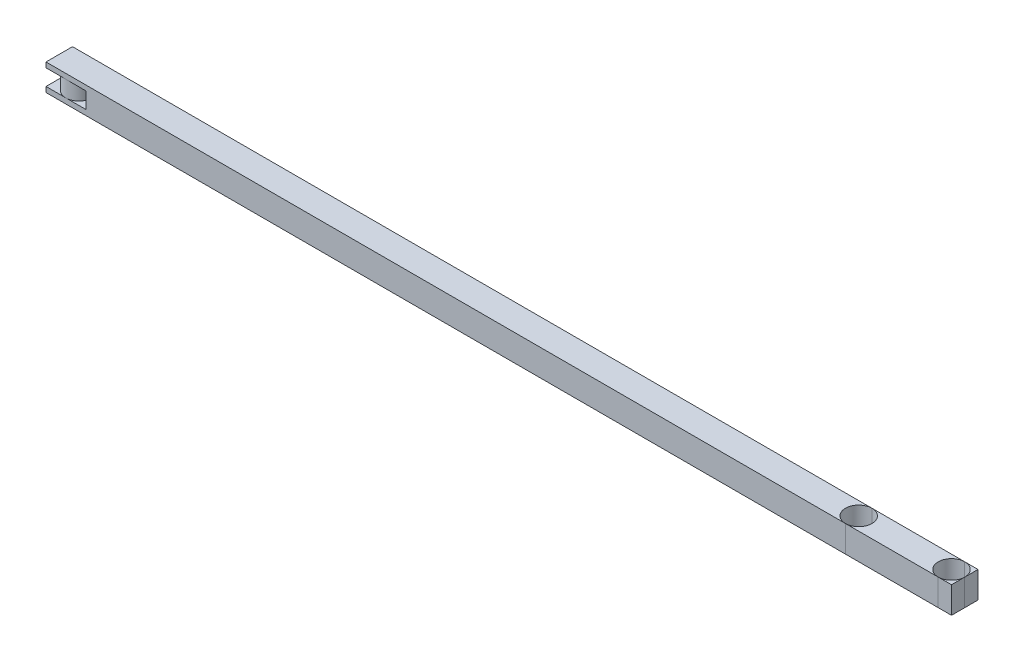
SolidWorks part; units mm, degrees
ref_plane "Front Plane" through (0, 0, 0) normal (0, 0, 1) x (1, 0, 0)
ref_plane "Top Plane" through (0, 0, 0) normal (0, 1, 0) x (1, 0, 0)
ref_plane "Right Plane" through (0, 0, 0) normal (1, 0, 0) x (0, 0, -1)
sketch "Sketch1" plane through (0, 0, 0) normal (0, 0, 1) x (1, 0, 0)
  line L0 (0, 0) -> (170.8, 0)
  line L2 (170.8, -5) -> (0, -5)
  line L3 (0, -5) -> (0, -4)
  line L4 (0, -0.9587) -> (7.5, -0.9587)
  line L5 (7.5, -0.9587) -> (7.5, -4)
  line L6 (7.5, -4) -> (0, -4)
  line L7 (0, -0.9587) -> (0, 0)
  line L12 (170.8, 0) -> (170.8, -5)
  dimension "D1" = 170.8
  dimension "D2" = 5
  dimension "D3" = 7.5
  dimension "D4" = 1
extrude "Boss-Extrude1" add sketch "Sketch1" along normal blind 5
ref_plane "Plane2" through (0, -2.5, 0) normal (0, 1, 0) x (1, 0, 0)
sketch "Sketch8" plane through (0, -0.9587, 0) normal (0, -1, 0) x (1, 0, 0)
  line L0 (0, 5) -> (0, 0) construction
  line L1 (0, 5) -> (170.8, 5) construction
  circle A0 centre (3.75, 2.5) radius 2.5
  dimension "D1" = 5
  dimension "D2" = 3.75
extrude "Boss-Extrude4" add sketch "Sketch8" along normal up to surface (3.0413 mm away) contours A0 up to face at (3.75, -4, 2.5)
sketch "Sketch9" plane through (0, -5, 0) normal (0, -1, 0) x (1, 0, 0)
  line L0 (0, 5) -> (170.8, 5) construction
  line L1 (170.8, 5) -> (170.8, 0) construction
  circle A0 centre (168.3, 2.5) radius 2.5
  dimension "D1" = 5
extrude "Cut-Extrude1" cut sketch "Sketch9" against normal blind 10
sketch "Sketch10" plane through (0, 0, 0) normal (0, 1, 0) x (1, 0, 0)
  line L0 (170.8, -5) -> (170.8, -2.5) construction
  line L1 (168.3, 0) -> (0, 0) construction
  circle A0 centre (150.8, -2.5) radius 2.5
  dimension "D1" = 5
  dimension "D2" = 20
extrude "Cut-Extrude3" cut sketch "Sketch10" against normal blind 10
